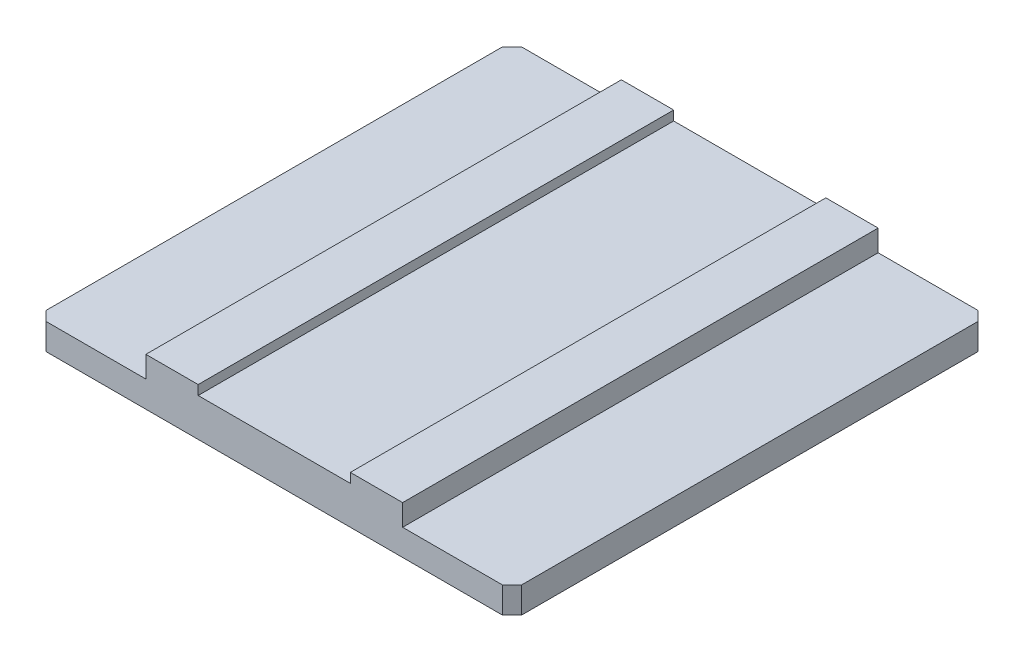
SolidWorks part; units mm, degrees
ref_plane "Front Plane" through (0, 0, 0) normal (0, 0, 1) x (1, 0, 0)
ref_plane "Top Plane" through (0, 0, 0) normal (0, 1, 0) x (1, 0, 0)
ref_plane "Right Plane" through (0, 0, 0) normal (1, 0, 0) x (0, 0, -1)
sketch "Sketch2" plane through (0, 0, 0) normal (0, 0, 1) x (1, 0, 0)
  line L0 (-50, 0) -> (50, 0)
  line L1 (50, 0) -> (50, 5.5)
  line L2 (50, 5.5) -> (27, 5.5)
  line L3 (27, 5.5) -> (27, 10)
  line L4 (27, 10) -> (16, 10)
  line L5 (16, 10) -> (16, 8)
  line L6 (16, 8) -> (-16, 8)
  line L7 (0, 8) -> (0, 0) construction
  line L8 (-16, 10) -> (-16, 8)
  line L9 (-27, 10) -> (-16, 10)
  line L10 (-27, 5.5) -> (-27, 10)
  line L11 (-50, 5.5) -> (-27, 5.5)
  line L12 (-50, 0) -> (-50, 5.5)
  dimension "D1" = 50
  dimension "D2" = 5.5
  dimension "D3" = 8
  dimension "D4" = 2
  dimension "D5" = 23
  dimension "D6" = 11
extrude "Boss-Extrude1" add sketch "Sketch2" along normal blind 100
chamfer "Chamfer1" distance 2 angle 45 4 edges at (-50, 2.75, 0) (50, 2.75, 0) (50, 2.75, 100) (-50, 2.75, 100)
